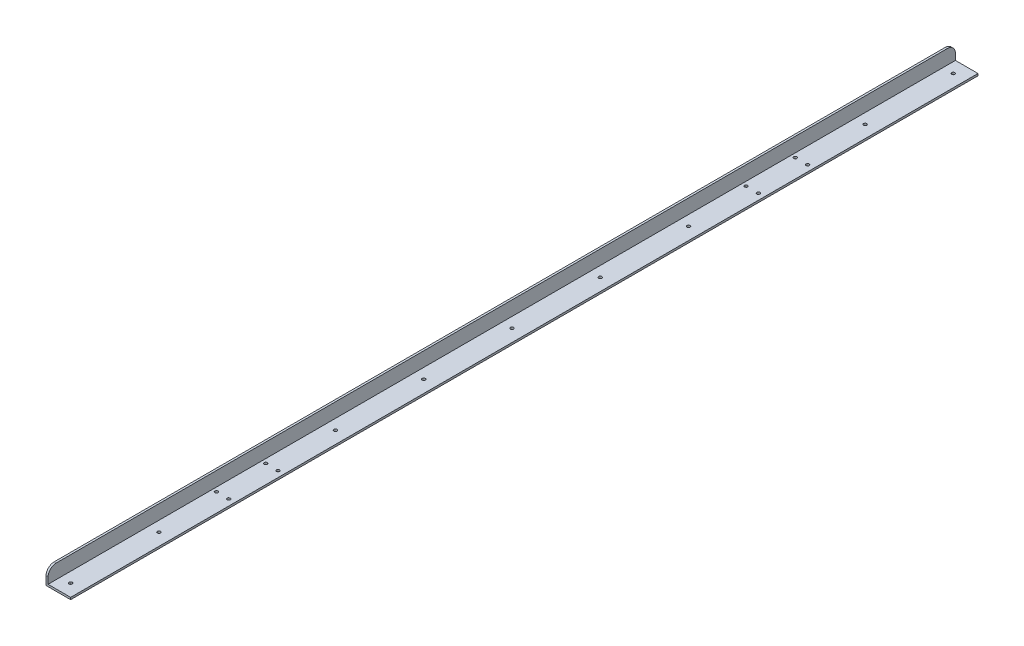
SolidWorks part; units mm, degrees
ref_plane "front" through (0, 0, 0) normal (0, 0, 1) x (1, 0, 0)
ref_plane "top" through (0, 0, 0) normal (0, 1, 0) x (1, 0, 0)
ref_plane "right" through (0, 0, 0) normal (1, 0, 0) x (0, 0, -1)
sketch "Sketch1" plane through (0, 0, 0) normal (0, 0, 1) x (1, 0, 0)
  line L0 (0, 0) -> (38.1, 0)
  line L1 (38.1, 0) -> (38.1, 3.175)
  line L2 (38.1, 3.175) -> (3.175, 3.175)
  line L3 (3.175, 3.175) -> (3.175, 25.4)
  line L4 (3.175, 25.4) -> (0, 25.4)
  line L5 (0, 25.4) -> (0, 0)
  dimension "D1" = 38.1
  dimension "D2" = 25.4
  dimension "D3" = 3.175
extrude "Extrude1" add sketch "Sketch1" against normal blind 1403.35
sketch "Sketch2" plane through (0, 0, 0) normal (0, 1, 0) x (1, 0, 0)
  line L0 (19.05, 19.05) -> (19.05, 1384.3) construction
  line L1 (38.1, 1403.35) -> (3.175, 1403.35) construction
  circle A0 centre (9.525, 254) radius 2.3876
  circle A1 centre (28.575, 254) radius 2.3876
  circle A2 centre (9.525, 1073.15) radius 2.3876
  circle A3 centre (28.575, 1073.15) radius 2.3876
  circle A4 centre (19.05, 19.05) radius 2.4257
  circle A5 centre (19.05, 155.575) radius 2.4257
  circle A6 centre (19.05, 428.625) radius 2.4257
  circle A7 centre (19.05, 565.15) radius 2.4257
  circle A9 centre (19.05, 701.675) radius 2.4257
  circle A10 centre (19.05, 838.2) radius 2.4257
  circle A11 centre (19.05, 974.725) radius 2.4257
  circle A12 centre (19.05, 1247.775) radius 2.4257
  circle A13 centre (19.05, 1384.3) radius 2.4257
  circle A14 centre (28.575, 330.2) radius 2.3876
  circle A15 centre (9.525, 330.2) radius 2.3876
  circle A16 centre (28.575, 1149.35) radius 2.3876
  circle A17 centre (9.525, 1149.35) radius 2.3876
  dimension "D2" = 4.7752
  dimension "D8" = 4.7752
  dimension "D5" = 4.8514
  dimension "D1" = 19.05
  dimension "D3" = 9.525
  dimension "D4" = 19.05
  dimension "D6" = 9.525
  dimension "D7" = 19.05
  dimension "D10" = 19.05
  dimension "D15" = 76.2
  dimension "D17" = 9.525
  dimension "D18" = 76.2
  dimension "D22" = 19.05
extrude "Cut-Extrude1" cut sketch "Sketch2" along normal through all
fillet "Fillet1" radius 12.7 2 edges at (1.5875, 25.4, -1403.35) (1.5875, 25.4, 0)
